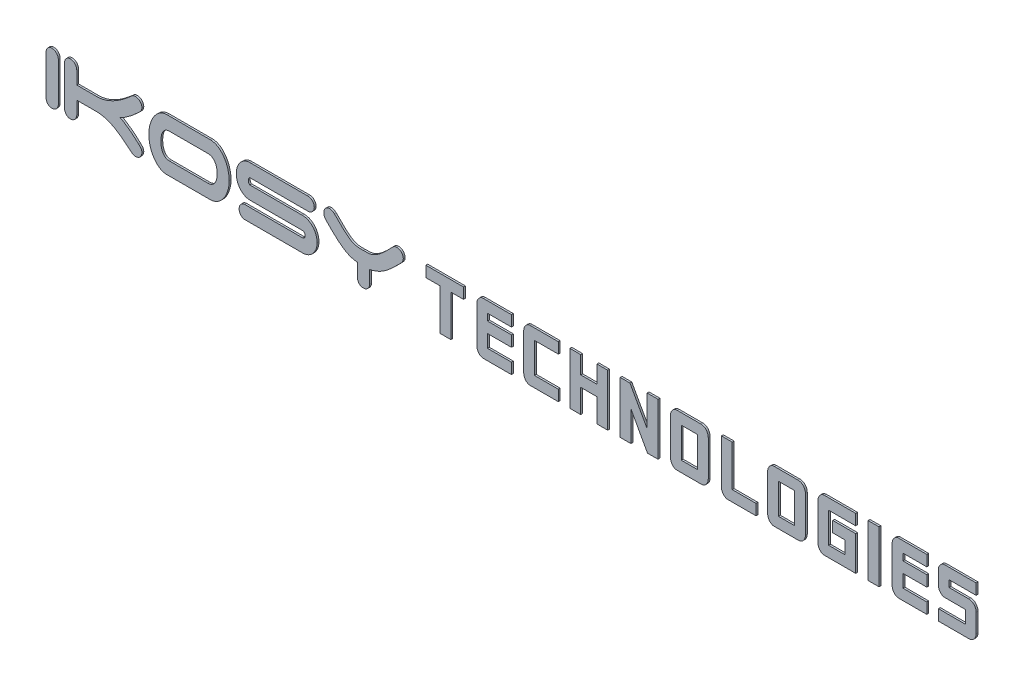
SolidWorks part; units mm, degrees
ref_plane "Front Plane" through (0, 0, 0) normal (0, 0, 1) x (1, 0, 0)
ref_plane "Top Plane" through (0, 0, 0) normal (0, 1, 0) x (1, 0, 0)
ref_plane "Right Plane" through (0, 0, 0) normal (1, 0, 0) x (0, 0, -1)
sketch "Text Sketch" plane through (0, 0, 0) normal (0, 0, 1) x (1, 0, 0)
  line L0 (158.0617, 381.3205) -> (790.3087, 381.3205) construction
  line L1 (-223.1193, 25.1941) -> (209.7014, 25.1941) construction
  line L2 (107.3834, 18.9017) -> (536.9168, 18.9017) construction
  text T0 "ikosy" font "Space Age" height 2.8
  text T1 "TECHNOLOGIES" font "Alien Encounters Solid" height 2.8
  dimension "D1" = 0.15
  dimension "D2" = 0.4
  dimension "D3" = 20.5
extrude "Text Extrude" add sketch "Text Sketch" along normal blind 0.1
